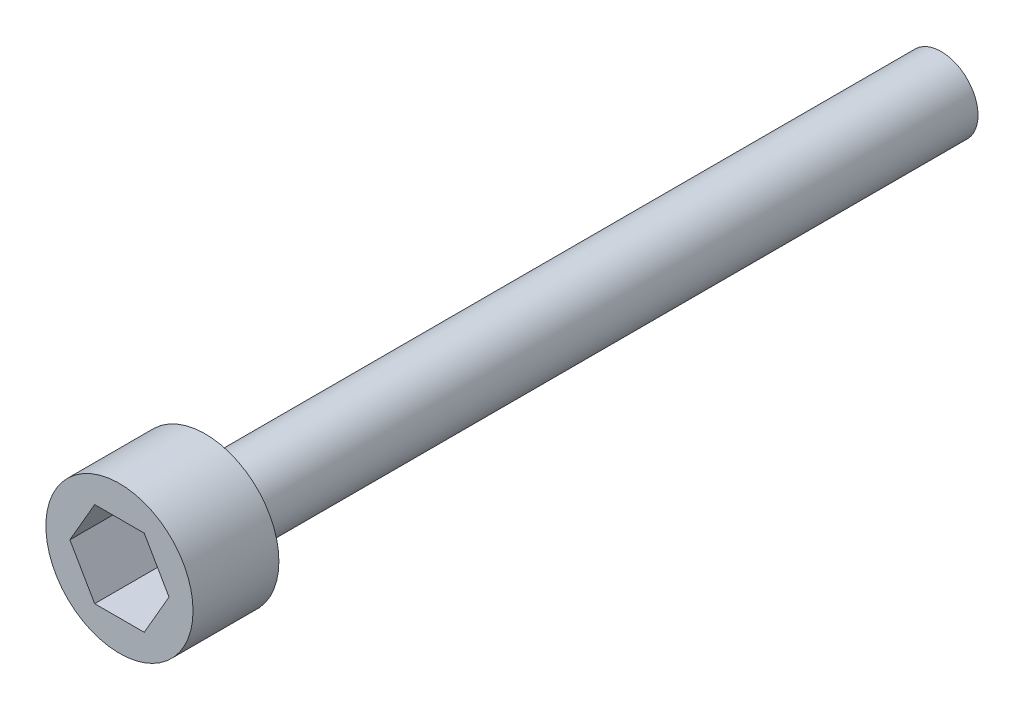
SolidWorks part; units mm, degrees
ref_plane "Front Plane" through (0, 0, 0) normal (0, 0, 1) x (1, 0, 0)
ref_plane "Top Plane" through (0, 0, 0) normal (0, 1, 0) x (1, 0, 0)
ref_plane "Right Plane" through (0, 0, 0) normal (1, 0, 0) x (0, 0, -1)
sketch "Sketch1" plane through (0, 0, 0) normal (0, 0, 1) x (1, 0, 0)
  circle A0 centre (0, 0) radius 3
  dimension "D1" = 6
extrude "Head Boss-Extrude1" add sketch "Sketch1" along normal blind 3.5
sketch "Sketch3" plane through (0, 0, 3.5) normal (0, 0, 1) x (1, 0, 0)
  line L0 (-1.0104, 1.75) -> (1.0104, 1.75)
  line L1 (1.0104, 1.75) -> (2.0207, 0)
  line L2 (2.0207, 0) -> (1.0104, -1.75)
  line L3 (1.0104, -1.75) -> (-1.0104, -1.75)
  line L4 (-1.0104, -1.75) -> (-2.0207, 0)
  line L5 (-2.0207, 0) -> (-1.0104, 1.75)
  line L6 (-2.0207, 0) -> (0, 0) construction
  line L7 (2.0207, 0) -> (0, 0) construction
  line L8 (-1.0104, -1.75) -> (0, 0) construction
  line L9 (0, 0) -> (1.0104, 1.75) construction
  line L10 (-1.0104, 1.75) -> (0, 0) construction
  line L11 (0, 0) -> (1.0104, -1.75) construction
  dimension "D1" = 60
  dimension "D2" = 60
  dimension "D3" = 60
  dimension "D4" = 60
  dimension "D5" = 60
  dimension "D6" = 3.5
extrude "Head Hex Cut-Extrude1" cut sketch "Sketch3" against normal blind 2.8
sketch "Sketch2" plane through (0, 0, 0) normal (0, 0, 1) x (1, 0, 0)
  circle A0 centre (0, 0) radius 1.5
  dimension "D1" = 3
extrude "Screw Boss-Extrude2" add sketch "Sketch2" against normal blind 30
